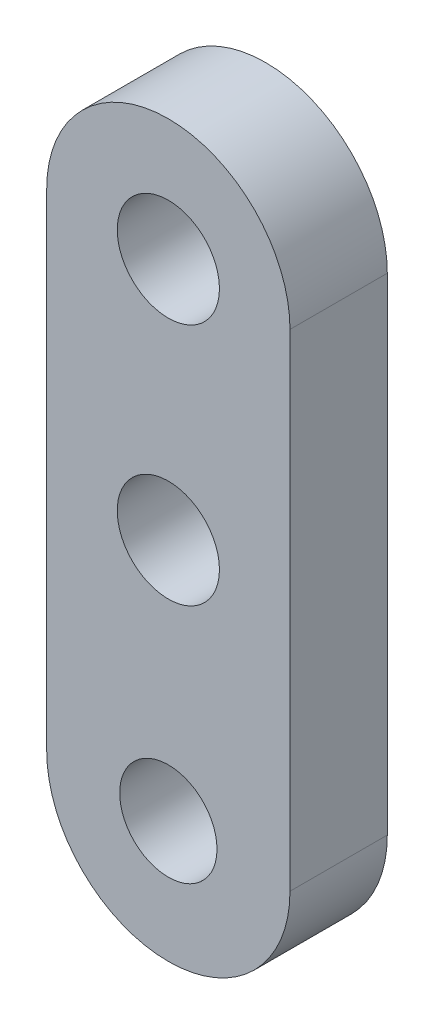
SolidWorks part; units mm, degrees
ref_plane "前视基准面" through (0, 0, 0) normal (0, 0, 1) x (1, 0, 0)
ref_plane "上视基准面" through (0, 0, 0) normal (0, 1, 0) x (1, 0, 0)
ref_plane "右视基准面" through (0, 0, 0) normal (1, 0, 0) x (0, 0, -1)
sketch "草图1" plane through (0, 0, 0) normal (0, 0, 1) x (1, 0, 0)
  line L0 (0, 0) -> (0, 10) construction
  line L1 (-2.5, 0) -> (-2.5, 10)
  line L2 (2.5, 0) -> (2.5, 10)
  circle A0 centre (0, 0) radius 1
  arc A2 (-2.5, 0) -> (2.5, 0) centre (0, 0) ccw
  arc A3 (2.5, 10) -> (-2.5, 10) centre (0, 10) ccw
  circle A4 centre (0, 10) radius 1.05
  circle A5 centre (0, 5) radius 1.05
  point P4 (0, 5)
  dimension "D1" = 2
  dimension "D2" = 2.1
  dimension "D3" = 2.5
  dimension "D5" = 2.1
  dimension "D4" = 10
extrude "凸台-拉伸1" add sketch "草图1" along normal blind 2
